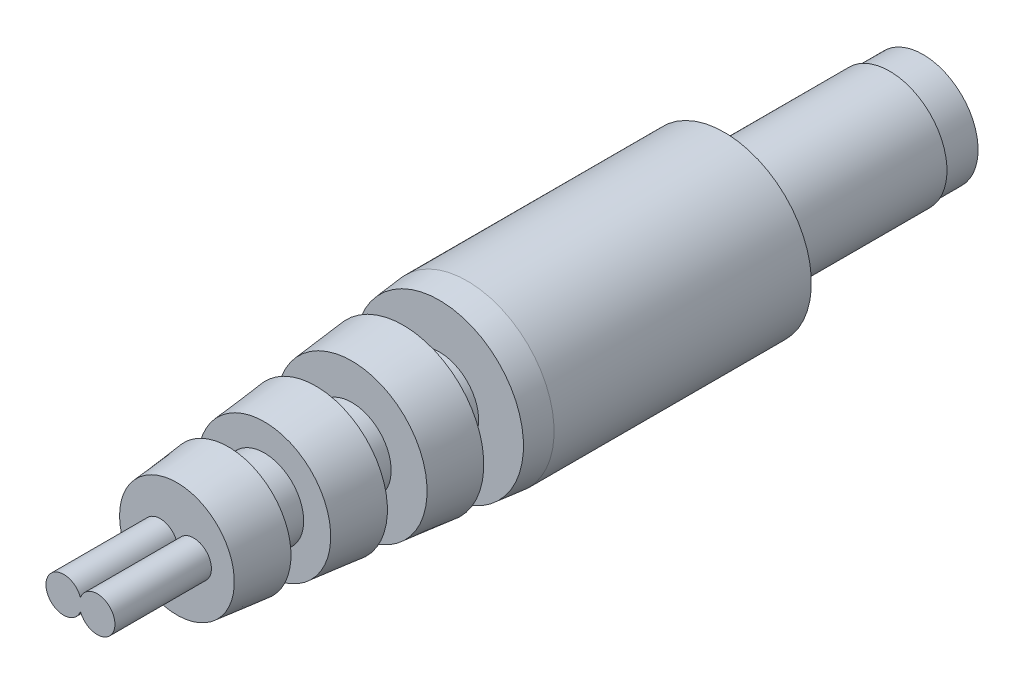
SolidWorks part; units mm, degrees
ref_plane "Front Plane" through (0, 0, 0) normal (0, 0, 1) x (1, 0, 0)
ref_plane "Top Plane" through (0, 0, 0) normal (0, 1, 0) x (1, 0, 0)
ref_plane "Right Plane" through (0, 0, 0) normal (1, 0, 0) x (0, 0, -1)
sketch "Sketch1" plane through (0, 0, 0) normal (1, 0, 0) x (0, 0, -1)
  line L0 (0, 0) -> (-36.83, 0) construction
  line L1 (-36.83, 0) -> (0, 0) construction
  line L2 (0, 0) -> (0, 2.7178)
  line L3 (0, 2.7178) -> (-1.651, 2.7178)
  line L4 (-1.651, 2.8321) -> (-1.651, 2.7178)
  line L5 (0, 0) -> (-36.83, 0)
  line L6 (-1.651, 2.8321) -> (-9.8044, 2.8321)
  line L7 (-9.8044, 2.8321) -> (-9.8044, 4.2926) construction
  line L8 (-9.8044, 2.8321) -> (-9.8044, 4.2926)
  line L9 (-9.8044, 4.2926) -> (-22.5044, 4.2926)
  line L10 (-23.876, 4.1528) -> (-22.5044, 4.2926) construction
  line L11 (-36.83, 0) -> (-36.83, 2.8321)
  line L12 (-36.83, 2.8321) -> (-34.29, 3.0911) construction
  line L13 (-36.83, 2.8321) -> (-34.29, 3.0911)
  line L15 (-34.29, 3.0911) -> (-34.29, 1.9389) construction
  line L16 (-34.29, 1.9389) -> (-32.512, 1.9389) construction
  line L17 (-32.512, 3.2723) -> (-32.512, 1.9389) construction
  line L18 (-32.512, 3.2723) -> (-29.972, 3.5313) construction
  line L19 (-29.972, 3.5313) -> (-29.972, 1.9389) construction
  line L20 (-29.972, 1.9389) -> (-28.194, 1.9389) construction
  line L21 (-28.194, 3.7125) -> (-28.194, 1.9389) construction
  line L22 (-28.194, 3.7125) -> (-25.654, 3.9715) construction
  line L23 (-25.654, 3.9715) -> (-25.654, 1.9389) construction
  line L24 (-25.654, 1.9389) -> (-23.876, 1.9389) construction
  line L25 (-23.876, 4.1528) -> (-23.876, 1.9389) construction
  line L26 (-34.29, 3.0911) -> (-34.29, 1.9389)
  line L27 (-34.29, 1.9389) -> (-32.512, 1.9389)
  line L28 (-32.512, 1.9389) -> (-32.512, 3.2723)
  line L29 (-32.512, 3.2723) -> (-29.972, 3.5313)
  line L30 (-29.972, 3.5313) -> (-29.972, 1.9389)
  line L31 (-29.972, 1.9389) -> (-28.194, 1.9389)
  line L32 (-28.194, 1.9389) -> (-28.194, 3.7125)
  line L33 (-28.194, 3.7125) -> (-25.654, 3.9715)
  line L34 (-25.654, 3.9715) -> (-25.654, 1.9389)
  line L35 (-25.654, 1.9389) -> (-23.876, 1.9389)
  line L36 (-23.876, 1.9389) -> (-23.876, 4.1528)
  line L37 (-23.876, 4.1528) -> (-22.5044, 4.2926)
  dimension "D1" = 36.83
  dimension "D2" = 2.7178
  dimension "D3" = 1.651
  dimension "D5" = 8.1534
  dimension "D7" = 12.7
  dimension "D9" = 2.54
  dimension "D10" = 2.54
  dimension "D11" = 2.54
revolve "Revolve6" add sketch "Sketch1" angle 360 about L5
sketch "Sketch2" plane through (0, 0, 0) normal (0, 0, -1) x (-1, 0, 0)
  circle A0 centre (0, 0) radius 1.1049
  dimension "D1" = 2.2098
extrude "Extrude1" cut sketch "Sketch2" against normal blind 10.16
sketch "Sketch4" plane through (0, 0, 36.83) normal (0, 0, 1) x (1, 0, 0)
  line L0 (0, 0) -> (0, 2.8321) construction
  line L1 (0, 2.8321) -> (0, -2.8321) construction
  line L2 (0, 0) -> (2.8321, 0) construction
  line L3 (2.8321, 0) -> (-2.8321, 0) construction
  line L4 (-1.7025, 0) -> (1.7025, 0) construction
  circle A0 centre (0, 0) radius 2.8321 construction
  arc A1 (0, -0.2919) -> (0, 0.2919) centre (0.8262, 0) ccw
  arc A2 (0, -0.2919) -> (0, 0.2919) centre (-0.8262, 0) cw
  dimension "D1" = 1.7526
  dimension "D2" = 0.8262
extrude "Extrude2" add sketch "Sketch4" along normal blind 4.7625
sketch "Sketch5" [suppressed] plane through (0, 0, 41.5925) normal (0, 0, 1) x (1, 0, 0)
  arc A2 (0, 0.2919) -> (0, -0.2919) centre (-0.8262, 0) ccw
  arc A3 (0, -0.2919) -> (0, 0.2919) centre (0.8262, 0) ccw
  arc A4 (0, 0.2919) -> (0, -0.2919) centre (-0.8262, 0) ccw
  arc A5 (0, -0.2919) -> (0, 0.2919) centre (0.8262, 0) ccw
  dimension "D1" = 0
sketch "Sketch6" [suppressed] plane through (0, 0, 0) normal (1, 0, 0) x (0, 0, -1)
  line L0 (-41.5925, 0) -> (-43.1419, 0)
  line L1 (-41.5925, 0.8763) -> (-41.5925, -0.8763) construction
  line L2 (-44.7294, -1.5875) -> (-44.7294, -6.8627)
  line L3 (-9.8044, -4.2926) -> (-9.8044, 4.2926) construction
  arc A0 (-43.1419, 0) -> (-44.7294, -1.5875) centre (-43.1419, -1.5875) ccw
  dimension "D1" = 1.5875
  dimension "D2" = 34.925
sweep "Sweep1" [suppressed] add profiles "Sketch5" path "Sketch6"
